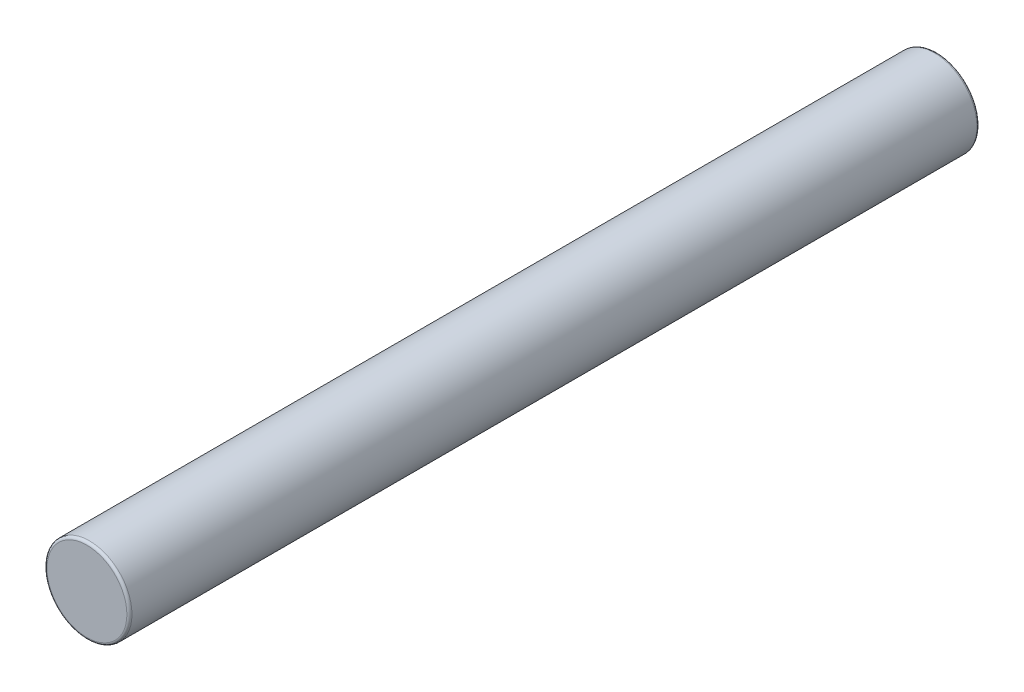
SolidWorks part; units mm, degrees
ref_plane "Front Plane" through (0, 0, 0) normal (0, 0, 1) x (1, 0, 0)
ref_plane "Top Plane" through (0, 0, 0) normal (0, 1, 0) x (1, 0, 0)
ref_plane "Right Plane" through (0, 0, 0) normal (1, 0, 0) x (0, 0, -1)
sketch "Sketch1" plane through (0, 0, 0) normal (0, 0, 1) x (1, 0, 0)
  circle A0 centre (0, 0) radius 5
  dimension "D1" = 10
extrude "Boss-Extrude1" add sketch "Sketch1" along normal mid plane 100
fillet "Fillet1" radius 0.3 2 edges at (5, 0, -50) (5, 0, 50)
